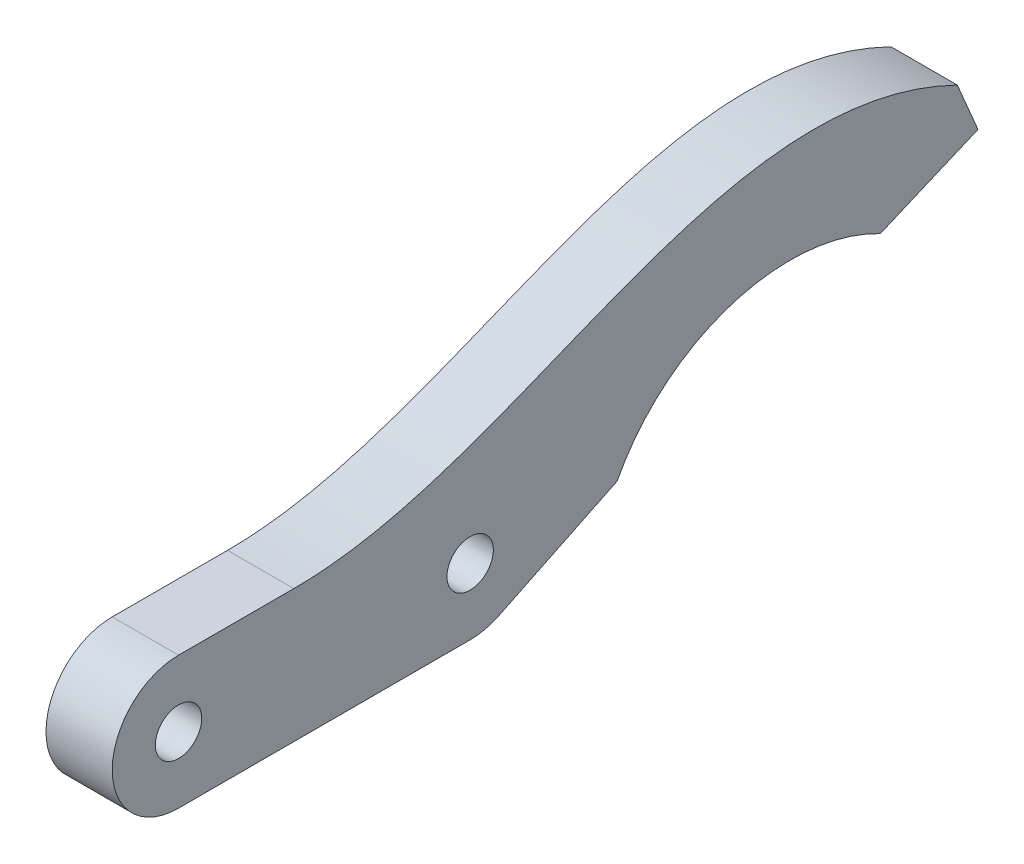
SolidWorks part; units mm, degrees
ref_plane "Front Plane" through (0, 0, 0) normal (0, 0, 1) x (1, 0, 0)
ref_plane "Top Plane" through (0, 0, 0) normal (0, 1, 0) x (1, 0, 0)
ref_plane "Right Plane" through (0, 0, 0) normal (1, 0, 0) x (0, 0, -1)
sketch "Sketch1" plane through (0, 0, 0) normal (1, 0, 0) x (0, 0, -1)
  line L1 (0, 0) -> (27, 0)
  line L2 (0, 0) -> (0, 10)
  line L3 (0, 10) -> (27, 10)
  circle A0 centre (5, 5) radius 1.75
  circle A1 centre (5, 5) radius 5
  circle A2 centre (27, 5) radius 5
  circle A3 centre (27, 5) radius 1.75
  dimension "D7" = 3.5
  dimension "D11" = 10
  dimension "D2" = 3.5
  dimension "D1" = 10
  dimension "D8" = 5
  dimension "D9" = 5
  dimension "D10" = 22
extrude "Boss-Extrude1" add sketch "Sketch1" along normal blind 5 contours A1 A0 | A2 L3 A1 L1 | A2 A3 | L2 A1 | L1 A1
sketch "Sketch2" plane through (5, 0, 0) normal (1, 0, 0) x (0, 0, -1)
  line L0 (57.948, 11.0678) -> (56.3872, 14.7507)
  line L6 (5, 10) -> (27, 10) construction
  line L14 (5, 10) -> (27, 10)
  line L20 (29.1838, 0.5021) -> (38.0854, 4.8241)
  line L21 (57.948, 11.0678) -> (65.3138, 14.1895)
  line L22 (65.3138, 14.1895) -> (63.753, 17.8724)
  arc A0 (38.0854, 4.8241) -> (57.948, 11.0678) centre (51.1386, -1.9853) cw
  arc A3 (27, 0) -> (27, 10) centre (27, 5) ccw construction
  arc A4 (27, 0) -> (27, 10) centre (27, 5) ccw
  spline S1 degree 3 poles (63.753, 17.8724) (45.9289, 26.5638) (31.0593, 10) (13.695, 10) knots 0 0 0 0 1 1 1 1
  point P2 (27, 5)
  dimension "D3" = 4
  dimension "D4" = 8
extrude "Boss-Extrude2" add sketch "Sketch2" against normal blind 5
